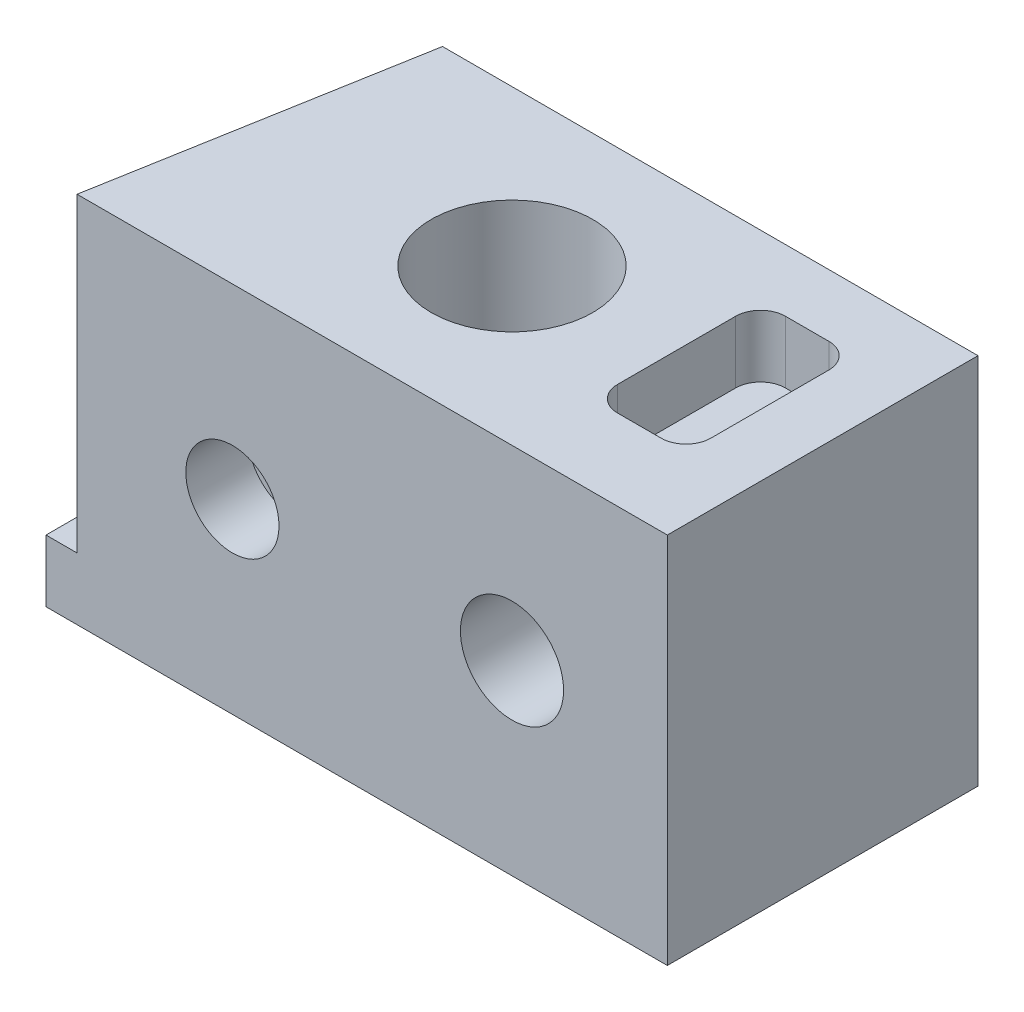
SolidWorks part; units mm, degrees
material "6061 Alloy"
ref_plane "Front Plane" through (0, 0, 0) normal (0, 0, 1) x (1, 0, 0)
ref_plane "Top Plane" through (0, 0, 0) normal (0, 1, 0) x (1, 0, 0)
ref_plane "Right Plane" through (0, 0, 0) normal (1, 0, 0) x (0, 0, -1)
sketch "Sketch1" plane through (0, 0, 0) normal (0, 1, 0) x (1, 0, 0)
  line L1 (-50, -25) -> (50, -25)
  line L2 (-50, -25) -> (-50, 25)
  line L3 (-50, 25) -> (50, 25)
  line L4 (50, -25) -> (50, 25)
  line L5 (-50, -25) -> (50, 25) construction
  line L6 (-50, 25) -> (50, -25) construction
  point P0 (0, 0)
  dimension "D1" = 100
  dimension "D2" = 50
extrude "Boss-Extrude1" add sketch "Sketch1" along normal blind 60
sketch "Sketch2" plane through (0, 60, 0) normal (0, 1, 0) x (1, 0, 0)
  line L0 (-50, -25) -> (50, -25) construction
  line L1 (-50, 25) -> (-36.1837, 25)
  line L2 (-50, 25) -> (-50, -25)
  line L3 (-50, -25) -> (-45, -25)
  line L4 (-36.1837, 25) -> (-45, -25)
  dimension "D1" = 5
  dimension "D2" = 100
extrude "Cut-Extrude1" cut sketch "Sketch2" against normal blind 50
sketch "Sketch3" plane through (0, 60, 0) normal (0, 1, 0) x (1, 0, 0)
  circle A0 centre (0, 0) radius 13
  dimension "D1" = 26
extrude "Cut-Extrude2" cut sketch "Sketch3" against normal blind 50
sketch "Sketch4" plane through (0, 0, 25) normal (0, 0, 1) x (1, 0, 0)
  line L0 (-50, 0) -> (50, 0) construction
  line L1 (50, 60) -> (50, 0) construction
  circle A0 centre (25, 30) radius 8.302
  dimension "D1" = 30
  dimension "D2" = 25
extrude "Cut-Extrude3" cut sketch "Sketch4" against normal through all
sketch "Sketch6" plane through (0, 60, 0) normal (0, 1, 0) x (1, 0, 0)
  line L0 (-45, -25) -> (50, -25) construction
  line L1 (29, 15) -> (36, 15)
  line L2 (25, 11) -> (25, -8)
  line L3 (29, -12) -> (36, -12)
  line L4 (40, 11) -> (40, -8)
  line L5 (50, -25) -> (50, 25) construction
  arc A0 (25, -8) -> (29, -12) centre (29, -8) ccw
  arc A1 (36, -12) -> (40, -8) centre (36, -8) ccw
  arc A2 (40, 11) -> (36, 15) centre (36, 11) ccw
  arc A3 (29, 15) -> (25, 11) centre (29, 11) ccw
  dimension "D1" = 4
  dimension "D2" = 10
  dimension "D3" = 13
  dimension "D4" = 10
  dimension "D5" = 15
extrude "Cut-Extrude4" cut sketch "Sketch6" against normal blind 10
sketch "Sketch7" plane through (0, 0, 25) normal (0, 0, 1) x (1, 0, 0)
  line L0 (25, 30) -> (-20, 30) construction
  circle A0 centre (-20, 30) radius 7.5
  dimension "D1" = 15
  dimension "D2" = 45
extrude "Cut-Extrude5" cut sketch "Sketch7" against normal blind 10
